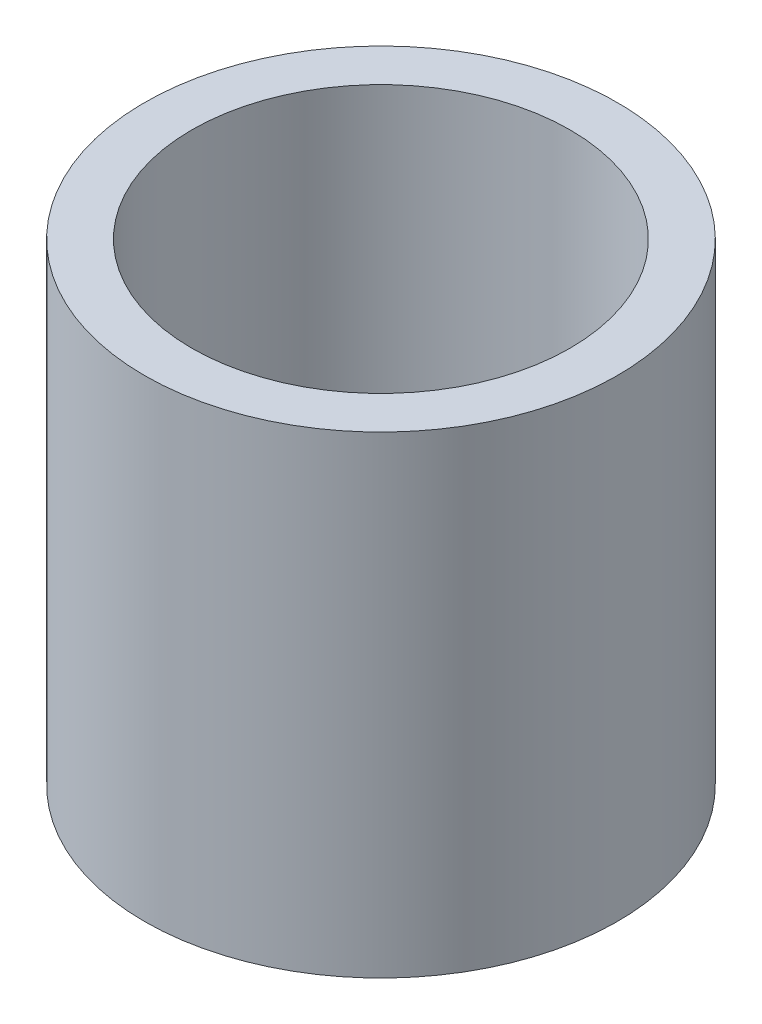
SolidWorks part; units mm, degrees
ref_plane "Front Plane" through (0, 0, 0) normal (0, 0, 1) x (1, 0, 0)
ref_plane "Top Plane" through (0, 0, 0) normal (0, 1, 0) x (1, 0, 0)
ref_plane "Right Plane" through (0, 0, 0) normal (1, 0, 0) x (0, 0, -1)
sketch "Sketch1" plane through (0, 0, 0) normal (0, 1, 0) x (1, 0, 0)
  circle A0 centre (0, 0) radius 4
  circle A1 centre (0, 0) radius 2.1
  dimension "D1" = 8
  dimension "D2" = 4.2
extrude "Boss-Extrude1" add sketch "Sketch1" along normal blind 4
sketch "Sketch2" plane through (0, 0, 0) normal (0, 1, 0) x (1, 0, 0)
  circle A0 centre (0, 0) radius 4
  circle A1 centre (0, 0) radius 5
  dimension "D1" = 10
extrude "Boss-Extrude2" add sketch "Sketch2" along normal blind 10
